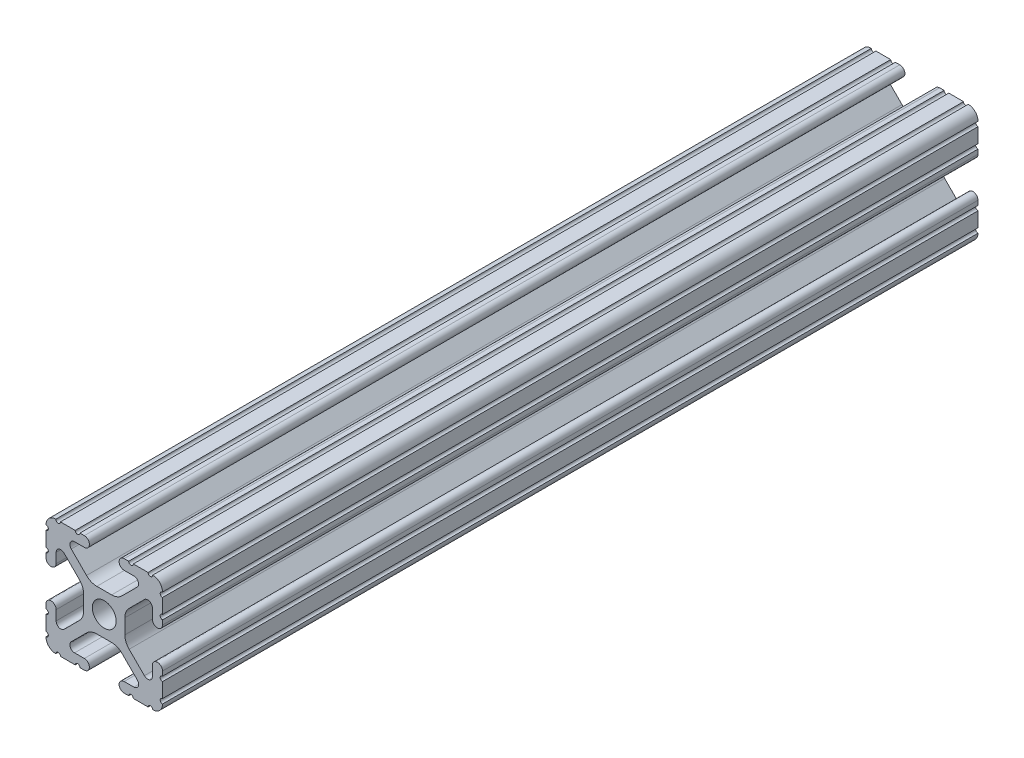
SolidWorks part; units mm, degrees
ref_plane "Front Plane" through (0, 0, 0) normal (0, 0, 1) x (1, 0, 0)
ref_plane "Top Plane" through (0, 0, 0) normal (0, 1, 0) x (1, 0, 0)
ref_plane "Right Plane" through (0, 0, 0) normal (1, 0, 0) x (0, 0, -1)
ref_plane "Plane1" through (0, 0, -25.4) normal (0, 0, -1) x (-1, 0, 0)
sketch "Sketch1" plane through (0, 0, -25.4) normal (0, 0, -1) x (-1, 0, 0)
  line L0 (12.7, -9.5504) -> (12.7, -6.3331)
  line L1 (12.7, -5.3171) -> (12.7, -4.3434)
  line L2 (10.4902, -4.3434) -> (10.4902, -6.4748)
  line L3 (8.7558, -7.1932) -> (5.4257, -3.8632)
  line L4 (4.4958, -1.6181) -> (4.4958, 1.6181)
  line L5 (5.4257, 3.8632) -> (8.7558, 7.1932)
  line L6 (10.4902, 6.4748) -> (10.4902, 4.3434)
  line L7 (12.7, 4.3434) -> (12.7, 5.3171)
  line L8 (12.7, 6.3331) -> (12.7, 9.5504)
  line L9 (9.5504, 12.7) -> (6.3331, 12.7)
  line L10 (5.3171, 12.7) -> (4.3434, 12.7)
  line L11 (4.3434, 10.4902) -> (6.4748, 10.4902)
  line L12 (7.1932, 8.7558) -> (3.8632, 5.4257)
  line L13 (1.6181, 4.4958) -> (-1.6181, 4.4958)
  line L14 (-3.8632, 5.4257) -> (-7.1932, 8.7558)
  line L15 (-6.4748, 10.4902) -> (-4.3434, 10.4902)
  line L16 (-4.3434, 12.7) -> (-5.3171, 12.7)
  line L17 (-6.3331, 12.7) -> (-9.5504, 12.7)
  line L18 (-12.7, 9.5504) -> (-12.7, 6.3331)
  line L19 (-12.7, 5.3171) -> (-12.7, 4.3434)
  line L20 (-10.4902, 4.3434) -> (-10.4902, 6.4748)
  line L21 (-8.7558, 7.1932) -> (-5.4257, 3.8632)
  line L22 (-4.4958, 1.6181) -> (-4.4958, -1.6181)
  line L23 (-5.4257, -3.8632) -> (-8.7558, -7.1932)
  line L24 (-10.4902, -6.4748) -> (-10.4902, -4.3434)
  line L25 (-12.7, -4.3434) -> (-12.7, -5.3171)
  line L26 (-12.7, -6.3331) -> (-12.7, -9.5504)
  line L27 (-9.5504, -12.7) -> (-6.3331, -12.7)
  line L28 (-5.3171, -12.7) -> (-4.3434, -12.7)
  line L29 (-4.3434, -10.4902) -> (-6.4748, -10.4902)
  line L30 (-7.1932, -8.7558) -> (-3.8632, -5.4257)
  line L31 (-1.6181, -4.4958) -> (1.6181, -4.4958)
  line L32 (3.8632, -5.4257) -> (7.1932, -8.7558)
  line L33 (6.4748, -10.4902) -> (4.3434, -10.4902)
  line L34 (4.3434, -12.7) -> (5.3171, -12.7)
  line L35 (6.3331, -12.7) -> (9.5504, -12.7)
  arc A0 (12.6998, -10.5664) -> (12.7, -9.5504) centre (12.7, -10.0584) cw
  arc A1 (12.7, -6.3331) -> (12.7, -5.3171) centre (12.7, -5.8251) cw
  arc A2 (12.7, -4.3434) -> (10.4902, -4.3434) centre (11.5951, -4.3434) ccw
  arc A3 (10.4902, -6.4748) -> (8.7558, -7.1932) centre (9.4742, -6.4748) cw
  arc A4 (5.4257, -3.8632) -> (4.4958, -1.6181) centre (7.6708, -1.6181) cw
  arc A5 (4.4958, 1.6181) -> (5.4257, 3.8632) centre (7.6708, 1.6181) cw
  arc A6 (8.7558, 7.1932) -> (10.4902, 6.4748) centre (9.4742, 6.4748) cw
  arc A7 (10.4902, 4.3434) -> (12.7, 4.3434) centre (11.5951, 4.3434) ccw
  arc A8 (12.7, 5.3171) -> (12.7, 6.3331) centre (12.7, 5.8251) cw
  arc A9 (12.7, 9.5504) -> (12.6998, 10.5664) centre (12.7, 10.0584) cw
  arc A10 (12.6998, 10.5664) -> (10.5664, 12.6998) centre (10.5918, 10.5918) ccw
  arc A11 (10.5664, 12.6998) -> (9.5504, 12.7) centre (10.0584, 12.7) cw
  arc A12 (6.3331, 12.7) -> (5.3171, 12.7) centre (5.8251, 12.7) cw
  arc A13 (4.3434, 12.7) -> (4.3434, 10.4902) centre (4.3434, 11.5951) ccw
  arc A14 (6.4748, 10.4902) -> (7.1932, 8.7558) centre (6.4748, 9.4742) cw
  arc A15 (3.8632, 5.4257) -> (1.6181, 4.4958) centre (1.6181, 7.6708) cw
  arc A16 (-1.6181, 4.4958) -> (-3.8632, 5.4257) centre (-1.6181, 7.6708) cw
  arc A17 (-7.1932, 8.7558) -> (-6.4748, 10.4902) centre (-6.4748, 9.4742) cw
  arc A18 (-4.3434, 10.4902) -> (-4.3434, 12.7) centre (-4.3434, 11.5951) ccw
  arc A19 (-5.3171, 12.7) -> (-6.3331, 12.7) centre (-5.8251, 12.7) cw
  arc A20 (-9.5504, 12.7) -> (-10.5664, 12.6998) centre (-10.0584, 12.7) cw
  arc A21 (-10.5664, 12.6998) -> (-12.6998, 10.5664) centre (-10.5918, 10.5918) ccw
  arc A22 (-12.6998, 10.5664) -> (-12.7, 9.5504) centre (-12.7, 10.0584) cw
  arc A23 (-12.7, 6.3331) -> (-12.7, 5.3171) centre (-12.7, 5.8251) cw
  arc A24 (-12.7, 4.3434) -> (-10.4902, 4.3434) centre (-11.5951, 4.3434) ccw
  arc A25 (-10.4902, 6.4748) -> (-8.7558, 7.1932) centre (-9.4742, 6.4748) cw
  arc A26 (-5.4257, 3.8632) -> (-4.4958, 1.6181) centre (-7.6708, 1.6181) cw
  arc A27 (-4.4958, -1.6181) -> (-5.4257, -3.8632) centre (-7.6708, -1.6181) cw
  arc A28 (-8.7558, -7.1932) -> (-10.4902, -6.4748) centre (-9.4742, -6.4748) cw
  arc A29 (-10.4902, -4.3434) -> (-12.7, -4.3434) centre (-11.5951, -4.3434) ccw
  arc A30 (-12.7, -5.3171) -> (-12.7, -6.3331) centre (-12.7, -5.8251) cw
  arc A31 (-12.7, -9.5504) -> (-12.6998, -10.5664) centre (-12.7, -10.0584) cw
  arc A32 (-12.6998, -10.5664) -> (-10.5664, -12.6998) centre (-10.5918, -10.5918) ccw
  arc A33 (-10.5664, -12.6998) -> (-9.5504, -12.7) centre (-10.0584, -12.7) cw
  arc A34 (-6.3331, -12.7) -> (-5.3171, -12.7) centre (-5.8251, -12.7) cw
  arc A35 (-4.3434, -12.7) -> (-4.3434, -10.4902) centre (-4.3434, -11.5951) ccw
  arc A36 (-6.4748, -10.4902) -> (-7.1932, -8.7558) centre (-6.4748, -9.4742) cw
  arc A37 (-3.8632, -5.4257) -> (-1.6181, -4.4958) centre (-1.6181, -7.6708) cw
  arc A38 (1.6181, -4.4958) -> (3.8632, -5.4257) centre (1.6181, -7.6708) cw
  arc A39 (7.1932, -8.7558) -> (6.4748, -10.4902) centre (6.4748, -9.4742) cw
  arc A40 (4.3434, -10.4902) -> (4.3434, -12.7) centre (4.3434, -11.5951) ccw
  arc A41 (5.3171, -12.7) -> (6.3331, -12.7) centre (5.8251, -12.7) cw
  arc A42 (9.5504, -12.7) -> (10.5664, -12.6998) centre (10.0584, -12.7) cw
  arc A43 (10.5664, -12.6998) -> (12.6998, -10.5664) centre (10.5918, -10.5918) ccw
  circle A44 centre (0, 0) radius 2.6035
extrude "Boss-Extrude1" add sketch "Sketch1" against normal blind 177.8
